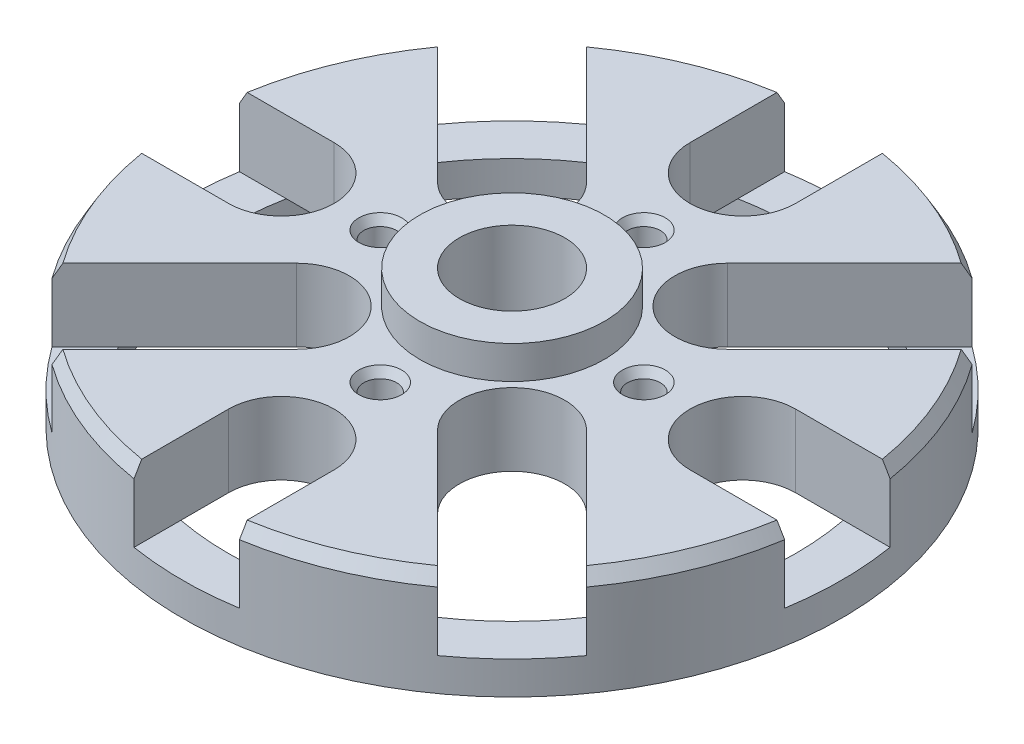
SolidWorks part; units mm, degrees
material "6061 Alloy"
ref_plane "Front" through (0, 0, 0) normal (0, 0, 1) x (1, 0, 0)
ref_plane "Top" through (0, 0, 0) normal (0, 1, 0) x (1, 0, 0)
ref_plane "Right" through (0, 0, 0) normal (1, 0, 0) x (0, 0, -1)
sketch "Sketch2" plane through (0, 0, 0) normal (0, 1, 0) x (1, 0, 0)
  circle A0 centre (0, 0) radius 25
  dimension "D1" = 50
extrude "Boss-Extrude1" add sketch "Sketch2" along normal blind 5.5
chamfer "Chamfer1" distance 1 angle 30 1 edges at (0, 5.5, 25)
sketch "Sketch3" plane through (0, 5.5, 0) normal (0, 1, 0) x (1, 0, 0)
  circle A0 centre (0, 0) radius 7
  dimension "D1" = 14
extrude "Boss-Extrude2" add sketch "Sketch3" along normal blind 2.5
hole_wizard "M3x0.5 Tapped Hole1" positions "Sketch5" profile "Sketch7" tap size "M3x0.5" standard "ANSI Metric" end condition through all
sketch "Sketch5" plane through (0, 5.5, 0) normal (0, 1, 0) x (1, 0, 0)
  line L0 (0, 10) -> (0, 0) construction
  point P0 (0, 10)
  dimension "D1" = 10
sketch "Sketch7" plane through (0, 5.5, -10) normal (1, 0, 0) x (0, 0, 1)
  line L0 (0, 0) -> (0, 5.5)
  line L1 (0, 5.5) -> (1.25, 5.5)
  line L2 (1.25, 5.5) -> (1.25, 0.6495)
  line L3 (1.25, 0.6495) -> (1.625, 0)
  line L5 (1.625, 0) -> (0, 0)
  line L6 (-1.25, 0.6495) -> (-1.625, 0) construction
  line L11 (0, -6.35) -> (0, 107.95) construction
  dimension "Thru Tap Drill Dia." = 2.5
  dimension "Thru Tap Drill Depth" = 5.5
  dimension "Near C'Sink Dia." = 3.25
  dimension "Near C'Sink Angle" = 60
cosmetic thread "Hole Thread1" parameters "D2"=3
sketch "Sketch8" plane through (0, 8, 0) normal (0, 1, 0) x (1, 0, 0)
  circle A0 centre (0, 0) radius 4
  dimension "D1" = 8
extrude "Cut-Extrude1" cut sketch "Sketch8" against normal through all
sketch "Sketch9" plane through (0, 5.5, 0) normal (0, 1, 0) x (1, 0, 0)
  line L0 (0, 32.5) -> (0, 17.5) construction
  line L1 (4, 32.5) -> (4, 17.5)
  line L2 (-4, 32.5) -> (-4, 17.5)
  circle A0 centre (0, 0) radius 25 construction
  arc A1 (4, 32.5) -> (-4, 32.5) centre (0, 32.5) ccw
  arc A2 (-4, 17.5) -> (4, 17.5) centre (0, 17.5) ccw
  circle A3 centre (0, 10) radius 1.25 construction
  point P6 (0, 25)
  point P11 (0, 13.5)
  dimension "D1" = 8
  dimension "D2" = 3.5
extrude "Cut-Extrude2" cut sketch "Sketch9" against normal through all
sketch "Sketch10" plane through (0, 5.5, 0) normal (0, 1, 0) x (1, 0, 0)
  line L0 (-26.3679, 26.3679) -> (-8.171, 8.171) construction
  line L1 (-23.5395, 29.1963) -> (-5.3425, 10.9994)
  line L2 (-29.1963, 23.5395) -> (-10.9994, 5.3425)
  line L3 (0, 0) -> (-8.171, 8.171) construction
  line L4 (0, 0) -> (0, 28.8522) construction
  arc A0 (-4, 24.0929) -> (4, 24.0929) centre (0, 0) ccw construction
  arc A1 (-23.5395, 29.1963) -> (-29.1963, 23.5395) centre (-26.3679, 26.3679) ccw
  arc A2 (-10.9994, 5.3425) -> (-5.3425, 10.9994) centre (-8.171, 8.171) ccw
  point P5 (-17.2694, 17.2694)
  dimension "D1" = 8
  dimension "D2" = 45
extrude "Cut-Extrude3" cut sketch "Sketch10" against normal through all
pattern_circular "CirPattern1" count 4 over 360 about axis through (0, 0, 0) along (0, 1, 0) of "M3x0.5 Tapped Hole1", "Cut-Extrude2", "Cut-Extrude3"
sketch "Sketch11" plane through (0, 0, 0) normal (0, -1, 0) x (1, 0, 0)
  circle A0 centre (0, 0) radius 25
  circle A1 centre (0, 0) radius 21.5
  dimension "D1" = 50
  dimension "D2" = 3.5
extrude "Boss-Extrude3" add sketch "Sketch11" along normal blind 2.5
